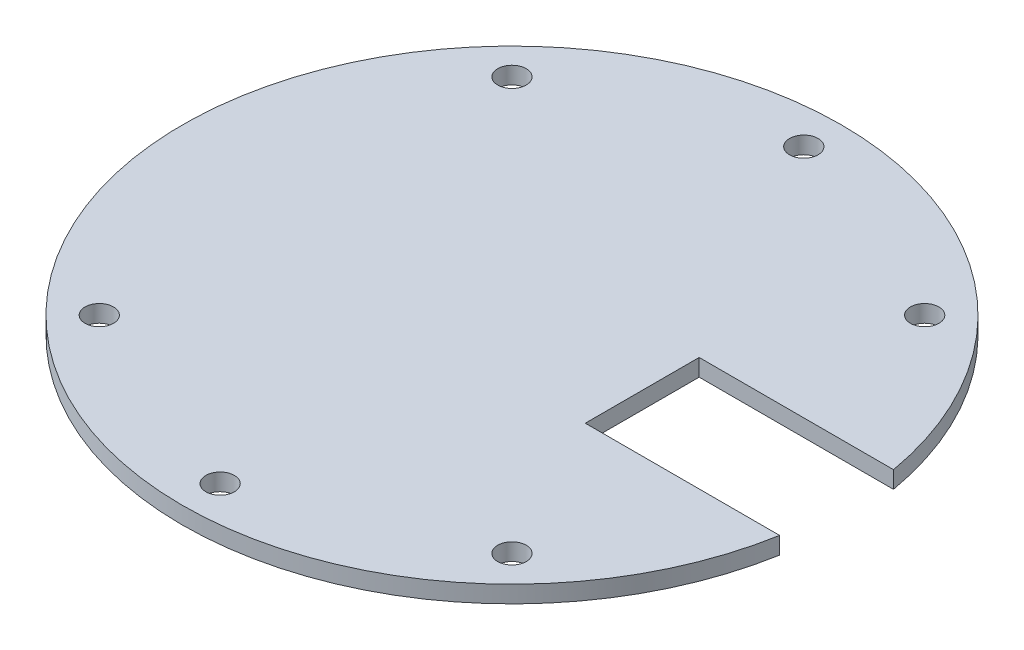
SolidWorks part; units mm, degrees
ref_plane "前视基准面" through (0, 0, 0) normal (0, 0, 1) x (1, 0, 0)
ref_plane "上视基准面" through (0, 0, 0) normal (0, 1, 0) x (1, 0, 0)
ref_plane "右视基准面" through (0, 0, 0) normal (1, 0, 0) x (0, 0, -1)
sketch "草图1" plane through (0, 0, 0) normal (0, 1, 0) x (1, 0, 0)
  circle A0 centre (0, 0) radius 23.15
  dimension "D1" = 46.3
extrude "凸台-拉伸1" add sketch "草图1" along normal blind 1.2
sketch "草图2" plane through (0, 1.2, 0) normal (0, 1, 0) x (1, 0, 0)
  line L0 (0, 25.9219) -> (0, -25.2757) construction
  line L1 (-26.0971, 0) -> (25.6107, 0) construction
  line L2 (23.15, 0) -> (23.15, 4)
  line L3 (23.15, 4) -> (9.15, 4)
  line L4 (9.15, 4) -> (9.15, -4)
  line L5 (9.15, -4) -> (23.15, -4)
  line L6 (23.15, -4) -> (23.15, 0)
  circle A0 centre (0, 0) radius 20.5 construction
  circle A1 centre (0, 20.5) radius 1
  circle A2 centre (14.4957, 14.4957) radius 1
  circle A4 centre (14.4957, -14.4957) radius 1
  circle A5 centre (0, -20.5) radius 1
  circle A6 centre (-14.4957, -14.4957) radius 1
  circle A8 centre (-14.4957, 14.4957) radius 1
  circle A9 centre (-20.5, 0) radius 1 [skipped]
  circle A10 centre (20.5, 0) radius 1 [skipped]
  circle A12 centre (0, 0) radius 23.15 construction
  point P26 (0, 0)
  dimension "D1" = 41
  dimension "D2" = 2
  dimension "D4" = 4
  dimension "D5" = 14
  dimension "D6" = 8
  dimension "D7" = 14
  dimension "D3" = 8
extrude "切除-拉伸1" cut sketch "草图2" against normal blind 1.6
